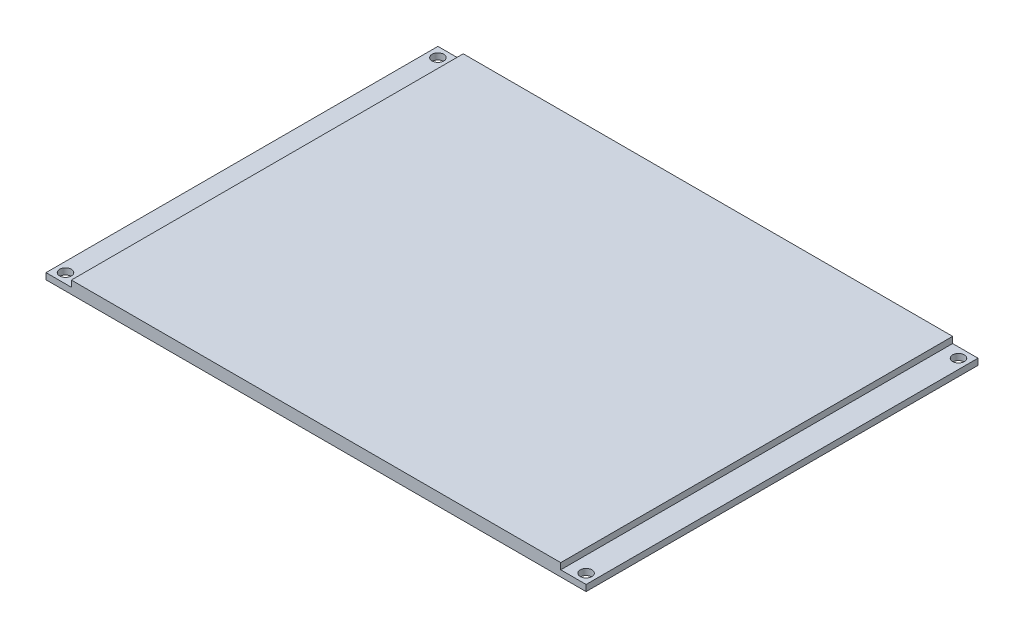
SolidWorks part; units mm, degrees
ref_plane "Front Plane" through (0, 0, 0) normal (0, 0, 1) x (1, 0, 0)
ref_plane "Top Plane" through (0, 0, 0) normal (0, 1, 0) x (1, 0, 0)
ref_plane "Right Plane" through (0, 0, 0) normal (1, 0, 0) x (0, 0, -1)
sketch "Sketch1" plane through (0, 0, 0) normal (0, 1, 0) x (1, 0, 0)
  line L0 (-69.25, 0) -> (69.25, 0) construction
  line L1 (-69.25, -50.25) -> (69.25, -50.25)
  line L2 (-69.25, -50.25) -> (-69.25, 50.25)
  line L3 (-69.25, 50.25) -> (69.25, 50.25)
  line L4 (69.25, -50.25) -> (69.25, 50.25)
  line L5 (-69.25, -50.25) -> (69.25, 50.25) construction
  line L6 (-69.25, 50.25) -> (69.25, -50.25) construction
  line L7 (0, 50.25) -> (0, -50.25) construction
  circle A0 centre (66.75, -47.75) radius 1.5
  circle A1 centre (66.75, 47.75) radius 1.5
  circle A2 centre (-66.75, -47.75) radius 1.5
  circle A3 centre (-66.75, 47.75) radius 1.5
  point P0 (0, 0)
  dimension "D3" = 3
  dimension "D1" = 138.5
  dimension "D2" = 100.5
  dimension "D4" = 2.5
  dimension "D5" = 2.5
extrude "Boss-Extrude1" add sketch "Sketch1" along normal blind 1.6 contours L1 L4 L3 L2 A3 A1 A0 A2
sketch "Sketch2" plane through (0, 1.6, 0) normal (0, 1, 0) x (1, 0, 0)
  line L0 (-62.75, 50.25) -> (-62.75, -50.25)
  line L1 (-69.25, 50.25) -> (69.25, 50.25) construction
  line L2 (-69.25, -50.25) -> (69.25, -50.25) construction
  line L3 (-62.75, -50.25) -> (62.75, -50.25)
  line L4 (62.75, -50.25) -> (62.75, 50.25)
  line L5 (62.75, 50.25) -> (-62.75, 50.25)
  line L6 (69.25, -50.25) -> (69.25, 50.25) construction
  line L7 (-69.25, -50.25) -> (-69.25, 50.25) construction
  dimension "D1" = 6.5
  dimension "D2" = 6.5
extrude "Boss-Extrude2" add sketch "Sketch2" along normal blind 1.6
sketch "Sketch3" plane through (0, 0, 0) normal (0, -1, 0) x (1, 0, 0)
  line L0 (-69.25, 50.25) -> (69.25, 50.25) construction
  line L1 (47.75, 10.25) -> (55.75, 10.25)
  line L2 (47.75, 10.25) -> (47.75, -9.75)
  line L3 (47.75, -9.75) -> (55.75, -9.75)
  line L4 (55.75, 10.25) -> (55.75, -9.75)
  line L5 (47.75, 10.25) -> (55.75, -9.75) construction
  line L6 (47.75, -9.75) -> (55.75, 10.25) construction
  line L7 (69.25, 50.25) -> (69.25, -50.25) construction
  point P0 (51.75, 0.25)
  dimension "D1" = 40
  dimension "D2" = 13.5
  dimension "D3" = 20
  dimension "D4" = 8
extrude "Boss-Extrude3" add sketch "Sketch3" along normal blind 6
